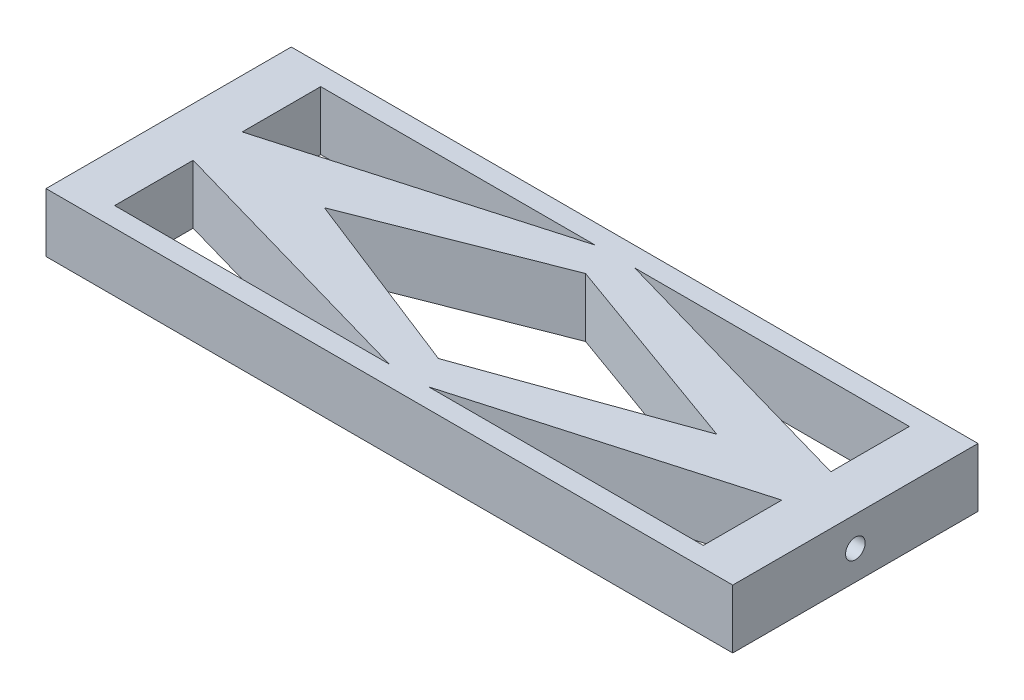
SolidWorks part; units mm, degrees
material "PLA"
ref_plane "Front" through (0, 0, 0) normal (0, 0, 1) x (1, 0, 0)
ref_plane "Top" through (0, 0, 0) normal (0, 1, 0) x (1, 0, 0)
ref_plane "Right" through (0, 0, 0) normal (1, 0, 0) x (0, 0, -1)
sketch "Sketch1" plane through (0, 0, 0) normal (0, 1, 0) x (1, 0, 0)
  line L1 (44.45, -15.875) -> (-44.45, -15.875)
  line L2 (44.45, -15.875) -> (44.45, 15.875)
  line L3 (44.45, 15.875) -> (-44.45, 15.875)
  line L4 (-44.45, -15.875) -> (-44.45, 15.875)
  line L5 (44.45, -15.875) -> (-44.45, 15.875) construction
  line L6 (44.45, 15.875) -> (-44.45, -15.875) construction
  point P0 (0, 0)
  dimension "D1" = 31.75
  dimension "D2" = 88.9
extrude "Boss-Extrude1" add sketch "Sketch1" along normal blind 7.62
sketch "Sketch2" plane through (0, 7.62, 0) normal (0, 1, 0) x (1, 0, 0)
  line L0 (-38.1, 3.175) -> (-38.1, 13.335)
  line L1 (-38.1, 13.335) -> (-2.564, 13.335)
  line L2 (-2.564, 13.335) -> (-38.1, 3.175)
  line L3 (44.45, 15.875) -> (-44.45, 15.875) construction
  line L4 (-44.45, 15.875) -> (-44.45, -15.875) construction
  line L5 (-38.1, -3.175) -> (-38.1, -13.335)
  line L6 (-38.1, -13.335) -> (-2.564, -13.335)
  line L7 (-2.564, -13.335) -> (-38.1, -3.175)
  line L8 (-44.45, -15.875) -> (44.45, -15.875) construction
  line L9 (2.54, 13.335) -> (38.1, 13.335)
  line L10 (38.1, 13.335) -> (38.1, 3.175)
  line L11 (38.1, 3.175) -> (2.54, 13.335)
  line L12 (44.45, -15.875) -> (44.45, 15.875) construction
  line L13 (38.1, -3.175) -> (38.1, -13.335)
  line L14 (38.1, -13.335) -> (2.54, -13.335)
  line L15 (2.54, -13.335) -> (38.1, -3.175)
  dimension "D1" = 10.16
  dimension "D2" = 2.54
  dimension "D3" = 6.35
  dimension "D4" = 35.536
  dimension "D5" = 35.536
  dimension "D6" = 2.54
  dimension "D7" = 10.16
  dimension "D8" = 35.56
  dimension "D9" = 6.35
  dimension "D10" = 10.16
  dimension "D11" = 35.56
  dimension "D12" = 10.16
extrude "Cut-Extrude1" cut sketch "Sketch2" against normal blind 29.464
sketch "Sketch3" plane through (0, 7.62, 0) normal (0, 1, 0) x (1, 0, 0)
  line L0 (0, 9.525) -> (-24.2924, 0)
  line L1 (0, -4.191) -> (0, 4.191) construction
  line L2 (-4.191, 0) -> (4.191, 0) construction
  line L3 (-24.2924, 0) -> (0, -9.525)
  line L4 (0, -9.525) -> (26.5076, 0)
  line L5 (26.5076, 0) -> (0, 9.525)
  line L6 (-44.45, -15.875) -> (44.45, -15.875) construction
  dimension "D1" = 50.8
  dimension "D2" = 19.05
  dimension "D3" = 6.35
extrude "Cut-Extrude2" cut sketch "Sketch3" against normal blind 29.464
sketch "Sketch4" plane through (44.45, 0, 0) normal (1, 0, 0) x (0, 0, -1)
  line L0 (0, 4.191) -> (0, -4.191) construction
  line L1 (17.4625, 0) -> (-17.4625, 0) construction
  circle A0 centre (0, 3.7869) radius 1.27
  dimension "D1" = 2.54
  dimension "D2" = 3.7869
extrude "Cut-Extrude3" cut sketch "Sketch4" against normal blind 7.62
sketch "Sketch5" plane through (-44.45, 0, 0) normal (-1, 0, 0) x (0, 0, 1)
  line L0 (0, -4.191) -> (0, 4.191) construction
  line L1 (17.4625, 0) -> (-17.4625, 0) construction
  circle A0 centre (0, 3.81) radius 1.27
  dimension "D1" = 2.54
  dimension "D2" = 3.81
extrude "Cut-Extrude4" cut sketch "Sketch5" against normal blind 7.62
